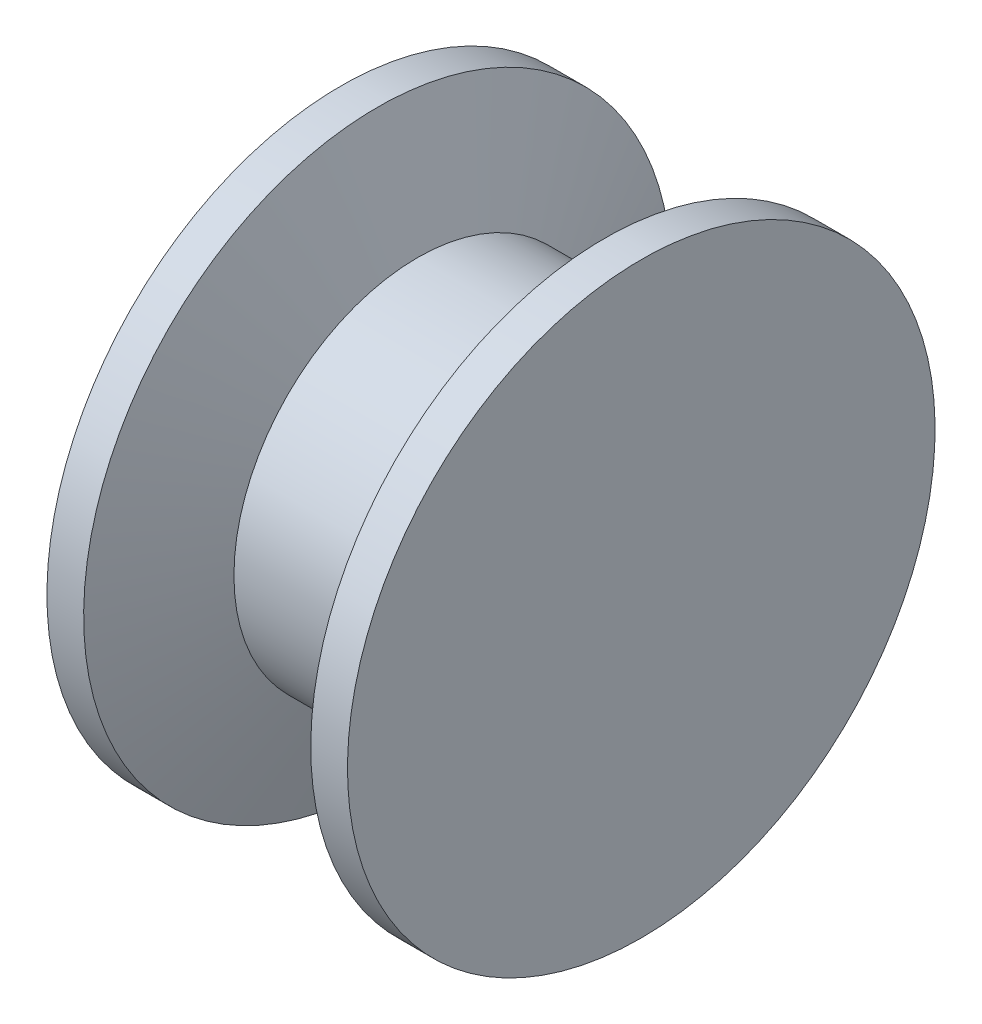
SolidWorks part; units mm, degrees
ref_plane "Front Plane" through (0, 0, 0) normal (0, 0, 1) x (1, 0, 0)
ref_plane "Top Plane" through (0, 0, 0) normal (0, 1, 0) x (1, 0, 0)
ref_plane "Right Plane" through (0, 0, 0) normal (1, 0, 0) x (0, 0, -1)
sketch "Sketch1" plane through (0, 0, 0) normal (0, 0, 1) x (1, 0, 0)
  line L0 (-39.4747, -10.2097) -> (15785.753, -10.2097) construction
  line L1 (0, 0) -> (0, 15825.2277) construction
  line L2 (-20.4596, 29.7903) -> (-15.4596, 29.7903)
  line L3 (-15.4596, 29.7903) -> (-10, 14.7903)
  line L4 (-10, 14.7903) -> (10, 14.7903)
  line L5 (-20.4596, 29.7903) -> (-20.4596, -10.2097)
  line L6 (20.4596, 29.7903) -> (20.4596, -10.2097)
  line L7 (15.4596, 29.7903) -> (10, 14.7903)
  line L8 (20.4596, 29.7903) -> (15.4596, 29.7903)
  line L9 (-20.4596, -10.2097) -> (20.4596, -10.2097)
  point P7 (0, 14.7903)
  point P14 (0, 14.7903)
  dimension "D1" = 5
  dimension "D2" = 20
  dimension "D3" = 10
  dimension "D4" = 40
  dimension "D5" = 15
  dimension "D6" = 14.7903
revolve "Revolve1" add sketch "Sketch1" angle 360 about L9
